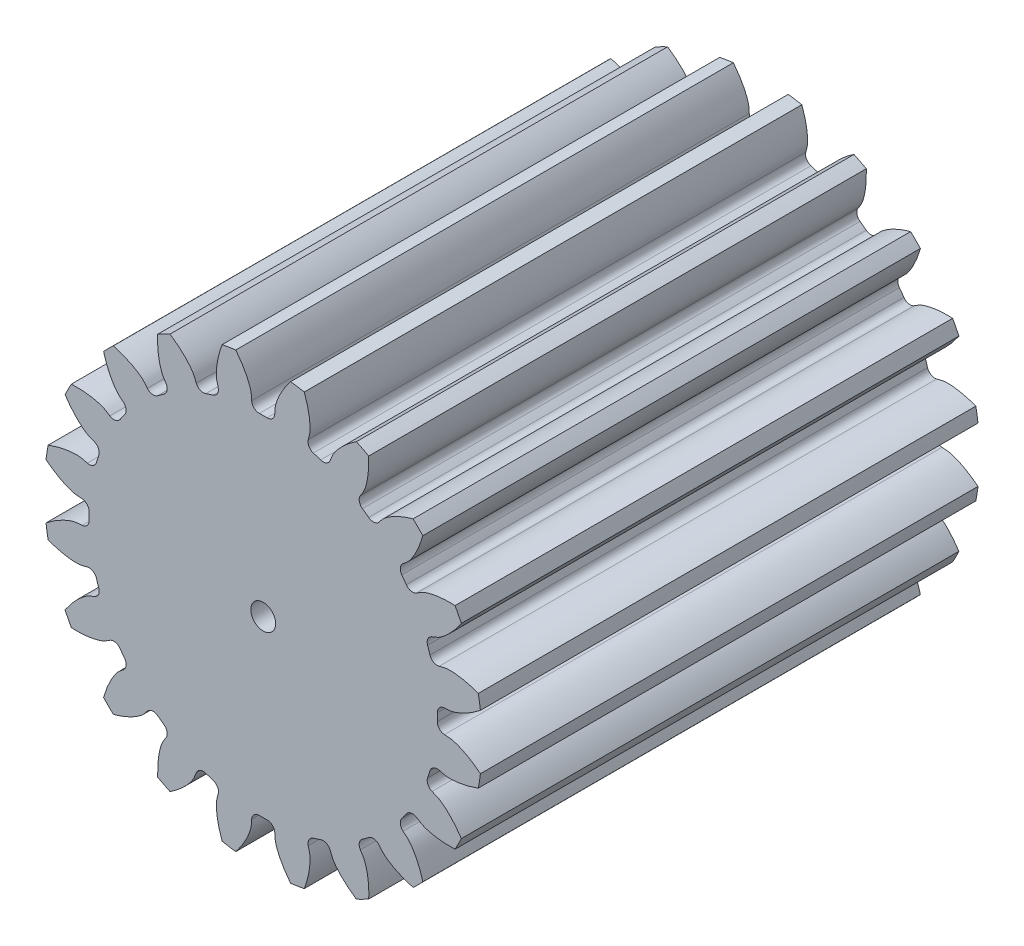
SolidWorks part; units mm, degrees
ref_plane "前视基准面" through (0, 0, 0) normal (0, 0, 1) x (1, 0, 0)
ref_plane "上视基准面" through (0, 0, 0) normal (0, 1, 0) x (1, 0, 0)
ref_plane "右视基准面" through (0, 0, 0) normal (1, 0, 0) x (0, 0, -1)
ref_axis "Axis1" through (0, 0, -88.99) along (0, 0, 1)
sketch "草图1" plane through (0, 0, 0) normal (0, 0, 1) x (1, 0, 0)
  circle A0 centre (0, 0) radius 8.8
extrude "LaShenA" add sketch "草图1" along normal blind 20
sketch "SketchA" plane through (0, 0, 20) normal (0, 0, 1) x (1, 0, 0)
  line L0 (0, 0) -> (0, 8.8) construction
  arc A0 (0.1541, 6.9983) -> (-0.1541, 6.9983) centre (0, 0) ccw
  arc A1 (1.4345, 9.1065) -> (-1.4345, 9.1065) centre (0, 0) ccw
  arc A2 (-0.1541, 6.9983) -> (-0.4643, 7.2835) centre (-0.1608, 7.3022) cw
  arc A3 (0.4643, 7.2835) -> (0.1541, 6.9983) centre (0.1608, 7.3022) cw
  circle A4 centre (0, 0) radius 7.5175 construction
  circle A5 centre (0, 0) radius 8.8 construction
  circle A6 centre (0, 0) radius 7 construction
  circle A7 centre (0, 0) radius 8 construction
  spline S0 degree 3 poles (0.4643, 7.2835) (0.4688, 7.3569) (0.4705, 7.453) (0.4864, 7.5587) (0.4963, 7.6034) (0.505, 7.6388) (0.5162, 7.6793) (0.5301, 7.7248) (0.5471, 7.7753) (0.5673, 7.8305) (0.5911, 7.8904) (0.6187, 7.9548) (0.6504, 8.0235) (0.6865, 8.0963) (0.7272, 8.173) (0.7727, 8.2535) (0.8232, 8.3375) (0.8791, 8.4248) (0.9405, 8.5152) (1.0076, 8.6084) (1.0806, 8.7043) (1.1597, 8.8024) (1.2759, 8.9389) (1.3693, 9.0397) (1.4345, 9.1065) knots 0.125068 0.125068 0.125068 0.125068 0.215847 0.244833 0.257593 0.272674 0.290074 0.309794 0.331834 0.356194 0.382875 0.411875 0.443195 0.476835 0.512796 0.551076 0.591676 0.634597 0.679837 0.727398 0.777278 0.829478 0.883999 1 1 1 1
  spline S1 degree 3 poles (-0.4643, 7.2835) (-0.4688, 7.3569) (-0.4705, 7.453) (-0.4864, 7.5587) (-0.4963, 7.6034) (-0.505, 7.6388) (-0.5162, 7.6793) (-0.5301, 7.7248) (-0.5471, 7.7753) (-0.5673, 7.8305) (-0.5911, 7.8904) (-0.6187, 7.9548) (-0.6504, 8.0235) (-0.6865, 8.0963) (-0.7272, 8.173) (-0.7727, 8.2535) (-0.8232, 8.3375) (-0.8791, 8.4248) (-0.9405, 8.5152) (-1.0076, 8.6084) (-1.0806, 8.7043) (-1.1597, 8.8024) (-1.2759, 8.9389) (-1.3693, 9.0397) (-1.4345, 9.1065) knots 0.125068 0.125068 0.125068 0.125068 0.215847 0.244833 0.257593 0.272674 0.290074 0.309794 0.331834 0.356194 0.382875 0.411875 0.443195 0.476835 0.512796 0.551076 0.591676 0.634597 0.679837 0.727398 0.777278 0.829478 0.883999 1 1 1 1
  dimension "D1" = 0.304
  dimension "Db" = 15.0351
  dimension "Da" = 17.6
  dimension "Df" = 14
  dimension "Dn" = 16
extrude "Cut-ExtrudeA" cut sketch "SketchA" against normal blind 20
pattern_circular "www.KYTool.cn" count 20 over 360 about axis through (0, 0, -88.99) along (0, 0, 1) of "Cut-ExtrudeA"
sketch "草图3" plane through (0, 0, 20) normal (0, 0, 1) x (1, 0, 0)
  circle A0 centre (0, 0) radius 0.5
  dimension "D1" = 1
extrude "切除-拉伸2" cut sketch "草图3" against normal through all
